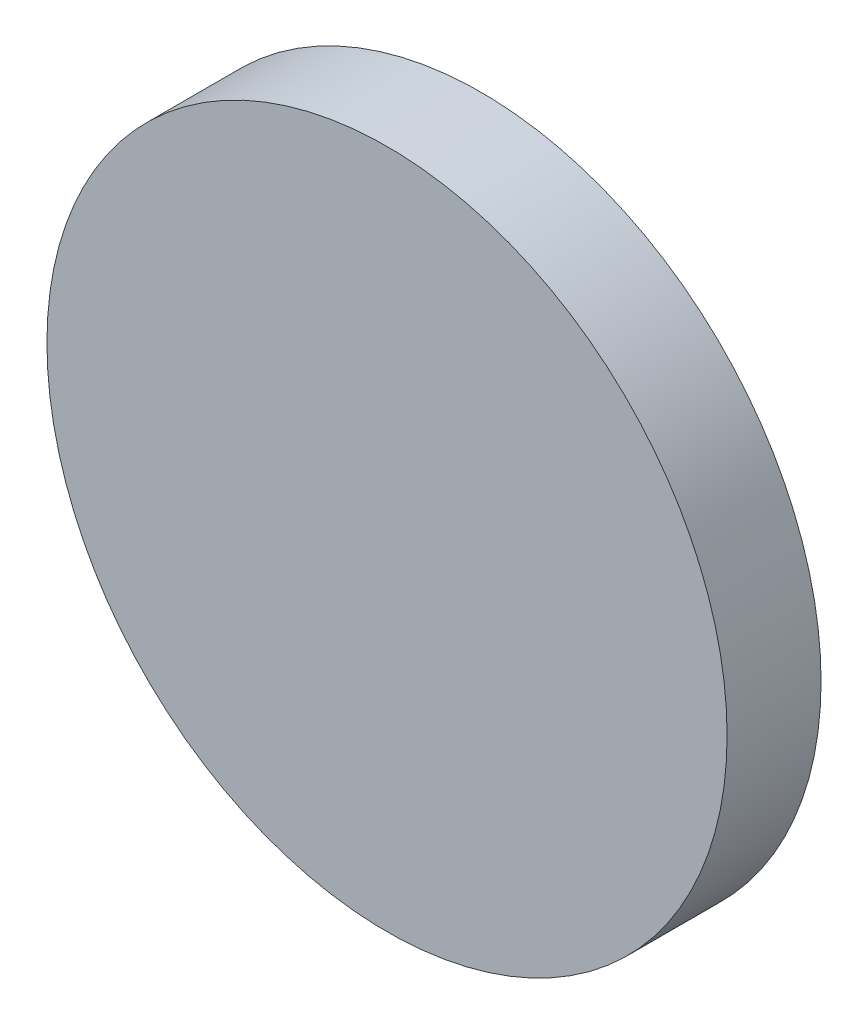
SolidWorks part; units mm, degrees
ref_plane "Front Plane" through (0, 0, 0) normal (0, 0, 1) x (1, 0, 0)
ref_plane "Top Plane" through (0, 0, 0) normal (0, 1, 0) x (1, 0, 0)
ref_plane "Right Plane" through (0, 0, 0) normal (1, 0, 0) x (0, 0, -1)
sketch "Sketch2" plane through (0, 0, 0) normal (0, 0, 1) x (1, 0, 0)
  circle A2 centre (0, 0) radius 11.4935
extrude "Boss-Extrude1" add sketch "Sketch2" along normal blind 3.175
